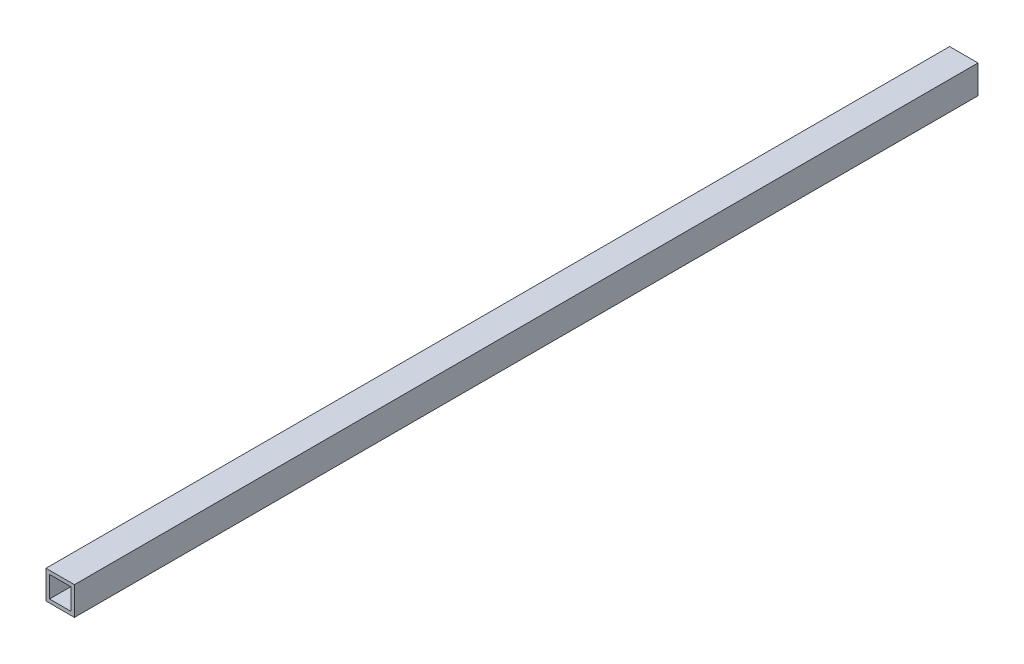
SolidWorks part; units mm, degrees
ref_plane "Front Plane" through (0, 0, 0) normal (0, 0, 1) x (1, 0, 0)
ref_plane "Top Plane" through (0, 0, 0) normal (0, 1, 0) x (1, 0, 0)
ref_plane "Right Plane" through (0, 0, 0) normal (1, 0, 0) x (0, 0, -1)
sketch "Sketch1" plane through (0, 0, 0) normal (0, 0, 1) x (1, 0, 0)
  line L0 (12.7, 0) -> (9.525, 0) construction
  line L1 (-12.7, 0) -> (12.7, 0) construction
  line L2 (0, 12.7) -> (0, -12.7)
  point P7 (0, 0)
sketch "Sketch2" plane through (0, 0, 0) normal (1, 0, 0) x (0, 0, -1)
  line L0 (403.86, 0) -> (-403.86, 0)
  point P4 (0, 0)
  dimension "Length" = 807.72
sketch "Sketch3" plane through (0, 0, 0) normal (0, 0, 1) x (1, 0, 0)
  line L0 (-12.7, 0) -> (12.7, 0) construction
  line L5 (12.7, -12.7) -> (-12.7, -12.7)
  line L6 (12.7, -12.7) -> (12.7, 12.7)
  line L11 (12.7, 12.7) -> (-12.7, 12.7)
  line L12 (-12.7, -12.7) -> (-12.7, 12.7)
  line L14 (12.7, -12.7) -> (-12.7, 12.7) construction
  line L15 (12.7, 12.7) -> (-12.7, -12.7) construction
  line L16 (9.525, -9.525) -> (-9.525, -9.525)
  line L17 (9.525, -9.525) -> (9.525, 9.525)
  line L18 (9.525, 9.525) -> (-9.525, 9.525)
  line L19 (-9.525, -9.525) -> (-9.525, 9.525)
  line L20 (9.525, -9.525) -> (-9.525, 9.525) construction
  line L21 (9.525, 9.525) -> (-9.525, -9.525) construction
  point P0 (0, 0)
  point P5 (0, 0)
  point P13 (9.525, -12.7)
  dimension "D1" = 3.175
  dimension "D3" = 25.4
  dimension "D4" = 25.4
extrude "Boss-Extrude1" add sketch "Sketch3" along normal up to vertex (403.86 mm away) and the other way up to vertex (403.86 mm away) up to point (0, 0, 403.86) other way up to point (0, 0, -403.86)
sketch "Sketch5" plane through (0, 0, 0) normal (1, 0, 0) x (0, 0, -1)
  line L0 (-403.86, 0) -> (403.86, 0) construction
  line L3 (-403.86, -12.7) -> (-403.86, 12.7) construction
  line L4 (403.86, -12.7) -> (403.86, 12.7) construction
  point P6 (-375.285, 0)
  point P7 (-365.76, 0)
  point P8 (365.76, 0)
  point P10 (375.285, 0)
  dimension "D1" = 28.575
  dimension "D2" = 38.1
  dimension "D3" = 28.575
  dimension "D4" = 38.1
equation "\"D1@Sketch3\"=\"Wall thickness@Sketch1\""
equation "\"D1@Sketch5\"=\"Width@Sketch1\"*1.125"
equation "\"D2@Sketch5\"=\"Width@Sketch1\"*1.5"
equation "\"D3@Sketch5\"=\"D1@Sketch5\""
equation "\"D4@Sketch5\"=\"D2@Sketch5\""
equation "\"D2@Sketch3\"=\"Wall Thickness@Sketch1\""
